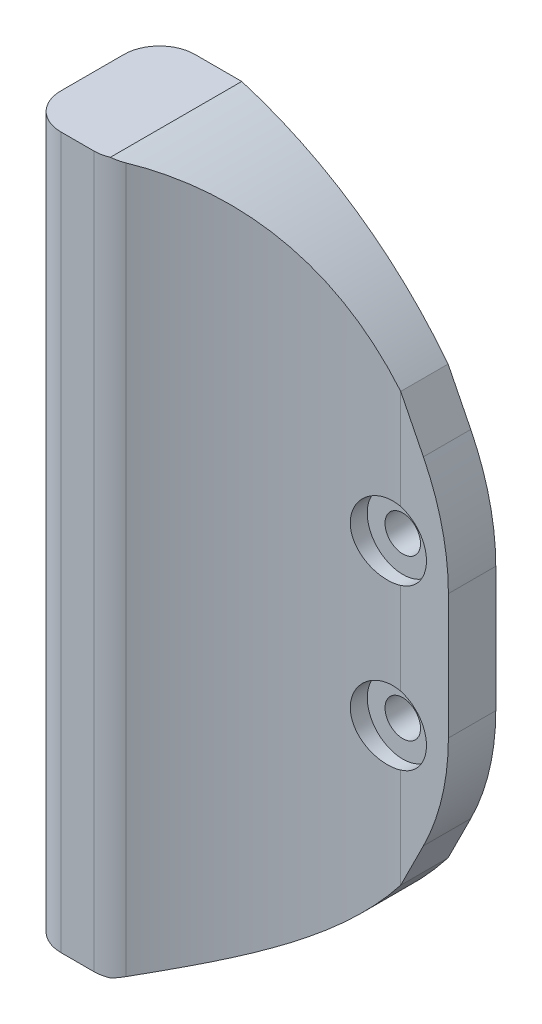
SolidWorks part; units mm, degrees
ref_plane "前视基准面" through (0, 0, 0) normal (0, 0, 1) x (1, 0, 0)
ref_plane "上视基准面" through (0, 0, 0) normal (0, 1, 0) x (1, 0, 0)
ref_plane "右视基准面" through (0, 0, 0) normal (1, 0, 0) x (0, 0, -1)
other "Configuration Table"
sketch "草图1" plane through (0, 0, 0) normal (0, 0, 1) x (1, 0, 0)
  line L1 (-17.6586, 30) -> (17.6586, 30)
  line L2 (-17.6586, 30) -> (-17.6586, -30)
  line L3 (-17.6586, -30) -> (17.6586, -30)
  line L4 (17.6586, 30) -> (17.6586, -30)
  line L5 (-17.6586, 30) -> (17.6586, -30) construction
  line L6 (-17.6586, -30) -> (17.6586, 30) construction
  circle A0 centre (0, 13.5) radius 1.5
  circle A1 centre (11.6913, 6.75) radius 1.5
  circle A2 centre (11.6913, -6.75) radius 1.5
  circle A3 centre (0, -13.5) radius 1.5
  circle A4 centre (-11.6913, -6.75) radius 1.5
  circle A5 centre (-11.6913, 6.75) radius 1.5
  point P14 (0, 0)
  point P18 (0, 0)
  dimension "D1" = 3
  dimension "D3" = 27
  dimension "D4" = 60
  dimension "D2" = 6
extrude "凸台-拉伸1" add sketch "草图1" along normal blind 8
sketch "草图2" plane through (0, 0, 8) normal (0, 0, 1) x (1, 0, 0)
  circle A0 centre (0, 13.5) radius 3
  circle A1 centre (11.6913, 6.75) radius 3
  circle A2 centre (11.6913, -6.75) radius 3
  circle A3 centre (0, -13.5) radius 3
  circle A4 centre (-11.6913, -6.75) radius 3
  circle A5 centre (-11.6913, 6.75) radius 3
  point P15 (0, 0)
  dimension "D1" = 6
  dimension "D2" = 6
extrude "切除-拉伸1" cut sketch "草图2" against normal blind 3
sketch "草图3" plane through (0, -30, 0) normal (0, -1, 0) x (1, 0, 0)
  line L0 (-17.6586, 0) -> (-35.2322, 0)
  line L1 (-35.2322, 0) -> (-35.2322, 11.3245)
  line L2 (-35.2322, 11.3245) -> (-23.3035, 11.3245)
  line L3 (-23.3035, 11.3245) -> (-17.6586, 8)
  line L4 (-17.6586, 0) -> (17.6586, 0)
  line L5 (17.6586, 0) -> (17.6586, 8)
  line L6 (17.6586, 8) -> (-17.6586, 8)
  line L7 (-17.6586, 8) -> (-17.6586, 0)
  line L8 (-17.6586, 0) -> (17.6586, 0)
  line L9 (17.6586, 0) -> (17.6586, 8)
  line L10 (17.6586, 8) -> (-17.6586, 8)
  line L11 (-17.6586, 8) -> (-17.6586, 0)
  line M9 (-17.6586, 8) -> (-17.6586, 0)
  dimension "D1" = 0
extrude "凸台-拉伸2" add sketch "草图3" against normal up to surface (60 mm away) contours L3 L2 L1 L0 M9 up to face at (0, 30, 4)
fillet "圆角1" radius 3 6 edges at (17.6586, 30, 4) (17.6586, -30, 4) (-17.6586, 0, 8) (-23.3035, 0, 11.3245) (-35.2322, 0, 0) (-35.2322, 0, 11.3245)
sketch "草图4" plane through (0, 0, 8) normal (0, 0, 1) x (1, 0, 0)
  circle A0 centre (0, 0) radius 5
  dimension "D1" = 10
extrude "切除-拉伸2" cut sketch "草图4" against normal through all
sketch "草图5" plane through (0, 0, 8) normal (0, 0, 1) x (1, 0, 0)
  line L0 (17.6586, -27) -> (17.6586, 27) construction
  line L1 (14.6586, 30) -> (-16.8409, 30) construction
  line L2 (-16.8409, -30) -> (14.6586, -30) construction
  line L3 (-16.8409, 30) -> (-18.3633, 30) construction
  line L4 (-18.3633, 30) -> (-18.3633, -30) construction
  line L5 (-18.3633, -30) -> (-16.8409, -30) construction
  line L6 (17.6586, -27) -> (17.6586, 27)
  line L7 (14.6586, 30) -> (-16.8409, 30)
  line L8 (-16.8409, -30) -> (14.6586, -30)
  line L9 (-16.8409, 30) -> (-18.3633, 30)
  line L10 (-18.3633, 30) -> (-18.3633, -30)
  line L11 (-18.3633, -30) -> (-16.8409, -30)
  line L12 (0, 0) -> (-13.5575, 0) construction
  line L13 (-16.8409, 30) -> (-6.8409, 10)
  line L14 (-6.8409, 10) -> (-6.8409, -10)
  line L15 (-16.8409, 30) -> (-16.8409, -30) construction
  line L16 (-16.8409, -30) -> (-6.8409, -10)
  arc A0 (17.6586, 27) -> (14.6586, 30) centre (14.6586, 27) ccw construction
  arc A1 (14.6586, -30) -> (17.6586, -27) centre (14.6586, -27) ccw construction
  arc A2 (17.6586, 27) -> (14.6586, 30) centre (14.6586, 27) ccw
  arc A3 (14.6586, -30) -> (17.6586, -27) centre (14.6586, -27) ccw
  point P11 (-7.5293, 11.3203)
  point P20 (-6.8409, 0)
  circle M4 centre (0, 0) radius 5
  circle M5 centre (0, 13.5) radius 3
  circle M8 centre (0, -13.5) radius 3
  circle M9 centre (11.6913, -6.75) radius 3
  circle M10 centre (11.6913, 6.75) radius 3
  line M11 (17.6586, -27) -> (17.6586, 27)
  arc M12 (17.6586, 27) -> (14.6586, 30) centre (14.6586, 27) ccw
  line M13 (14.6586, 30) -> (-16.8409, 30)
  line M15 (-16.8409, -30) -> (14.6586, -30)
  arc M16 (14.6586, -30) -> (17.6586, -27) centre (14.6586, -27) ccw
  dimension "D1" = 10
  dimension "D2" = 10
extrude "切除-拉伸3" cut sketch "草图5" against normal blind 10 contours L12 L14 L16 M11 M4 M15 M16 M8 M9 | L12 L6 L13 L14 M12 M13 M4 M5 M10 | M5 | M10 | M9 | M8
fillet "圆角2" radius 20 2 edges at (-6.8409, 10, 4) (-6.8409, -10, 4)
sketch "草图6" plane through (0, -30, 0) normal (0, -1, 0) x (1, 0, 0)
  line L0 (-8.9523, 0) -> (-6.8409, 0) construction
  line L1 (-6.8409, 0) -> (-6.8409, 8) construction
  line L2 (-6.8409, 8) -> (-8.9523, 8) construction
  line L3 (-16.8409, 0) -> (-8.9523, 0) construction
  line L4 (-8.9523, 8) -> (-16.8409, 8) construction
  line L5 (-16.8409, 0) -> (-16.8409, 8)
  line L6 (-18.3633, 8.415) -> (-22.5989, 10.9095)
  line L7 (-24.1213, 11.3245) -> (-32.2322, 11.3245)
  line L8 (-35.2322, 8.3245) -> (-35.2322, 3)
  line L9 (-32.2322, 0) -> (-16.8409, 0)
  line L10 (-16.8409, 0) -> (-16.8409, 8)
  line L11 (-18.3633, 8.415) -> (-22.5989, 10.9095)
  line L12 (-24.1213, 11.3245) -> (-32.2322, 11.3245)
  line L13 (-35.2322, 8.3245) -> (-35.2322, 3)
  line L14 (-32.2322, 0) -> (-16.8409, 0)
  line L15 (-16.8409, 8) -> (-16.8409, 0) construction
  line L16 (-8.9523, 0) -> (-6.8409, 0)
  line L17 (-6.8409, 0) -> (-6.8409, 8)
  line L18 (-6.8409, 8) -> (-8.9523, 8)
  line L19 (-16.8409, 0) -> (-8.9523, 0)
  line L20 (-8.9523, 8) -> (-16.8409, 8)
  line L21 (-16.8409, 8) -> (-16.8409, 0)
  line L22 (-18.3633, 8.415) -> (-10.8668, 4)
  line L23 (-10.8668, 4) -> (-6.8409, 4)
  line L24 (-28.2857, 11.3245) -> (-10.8668, 4)
  arc A4 (-18.3633, 8.415) -> (-16.8409, 8) centre (-16.8409, 11) ccw
  arc A5 (-22.5989, 10.9095) -> (-24.1213, 11.3245) centre (-24.1213, 8.3245) ccw
  arc A6 (-32.2322, 11.3245) -> (-35.2322, 8.3245) centre (-32.2322, 8.3245) ccw
  arc A7 (-35.2322, 3) -> (-32.2322, 0) centre (-32.2322, 3) ccw
  arc A8 (-18.3633, 8.415) -> (-16.8409, 8) centre (-16.8409, 11) ccw
  arc A9 (-22.5989, 10.9095) -> (-24.1213, 11.3245) centre (-24.1213, 8.3245) ccw
  arc A10 (-32.2322, 11.3245) -> (-35.2322, 8.3245) centre (-32.2322, 8.3245) ccw
  arc A11 (-35.2322, 3) -> (-32.2322, 0) centre (-32.2322, 3) ccw
  point P18 (-10.8668, 4)
  arc M13 (-16.8409, 8) -> (-18.3633, 8.415) centre (-16.8409, 11) cw
  line M14 (-18.3633, 8.415) -> (-22.5989, 10.9095)
  arc M15 (-22.5989, 10.9095) -> (-24.1213, 11.3245) centre (-24.1213, 8.3245) ccw
  line M16 (-24.1213, 11.3245) -> (-32.2322, 11.3245)
  dimension "D2" = 4
  dimension "D1" = 0
extrude "切除-拉伸4" cut sketch "草图6" against normal through all contours L22 L21 M13 | L22 L23 L17 L18 L20 L21 | L24 L21 L22 M16 M14 M15 | L21 L24 L22
sketch "草图7" plane through (0, 0, 5) normal (0, 0, 1) x (1, 0, 0)
  line L0 (-13.2449, -9.3164) -> (-13.2449, -4.1836) construction
  line L1 (-13.2449, 4.1836) -> (-13.2449, 9.3164) construction
  line L2 (-13.2449, -9.3164) -> (-13.2449, -4.1836)
  line L3 (-13.2449, 4.1836) -> (-13.2449, 9.3164)
  arc A0 (-13.2449, -4.1836) -> (-13.2449, -9.3164) centre (-11.6913, -6.75) ccw construction
  arc A1 (-13.2449, 9.3164) -> (-13.2449, 4.1836) centre (-11.6913, 6.75) ccw construction
  arc A2 (-13.2449, -4.1836) -> (-13.2449, -9.3164) centre (-11.6913, -6.75) ccw
  arc A3 (-13.2449, 9.3164) -> (-13.2449, 4.1836) centre (-11.6913, 6.75) ccw
  circle A4 centre (-11.6913, 6.75) radius 3
  circle A5 centre (-11.6913, -6.75) radius 3
  line M1 (-13.2449, 4.1836) -> (-13.2449, 9.3164)
  arc M2 (-13.2449, 9.3164) -> (-13.2449, 4.1836) centre (-11.6913, 6.75) ccw
extrude "切除-拉伸5" cut sketch "草图7" against normal blind 2 contours A4 M1 | M2 M1 | L2 A2 | L2 A5
sketch "草图8" plane through (0, 0, 11.3245) normal (0, 0, 1) x (1, 0, 0)
  line L0 (-10.8668, -18.0518) -> (-8.9523, -14.2229) construction
  line L1 (-6.8409, -5.2786) -> (-6.8409, 5.2786) construction
  line L2 (-8.9523, 14.2229) -> (-10.8668, 18.0518) construction
  line L3 (-10.8668, 18.0518) -> (-16.8409, 30) construction
  line L4 (-32.2322, -30) -> (-28.2857, -30)
  line L5 (-28.2857, -30) -> (-28.2857, 30)
  line L6 (-28.2857, 30) -> (-32.2322, 30)
  line L7 (-32.2322, 30) -> (-32.2322, -30)
  line L8 (-32.2322, -30) -> (-28.2857, -30)
  line L9 (-28.2857, -30) -> (-28.2857, 30)
  line L10 (-28.2857, 30) -> (-32.2322, 30)
  line L11 (-32.2322, 30) -> (-32.2322, -30)
  line L12 (-16.8409, 30) -> (-28.2857, 30) construction
  line L13 (-28.2857, 30) -> (-28.2857, -30) construction
  line L14 (-28.2857, -30) -> (-16.8409, -30) construction
  line L15 (-16.8409, -30) -> (-10.8668, -18.0518) construction
  line L16 (-10.8668, -18.0518) -> (-8.9523, -14.2229)
  line L17 (-6.8409, -5.2786) -> (-6.8409, 5.2786)
  line L18 (-8.9523, 14.2229) -> (-10.8668, 18.0518)
  line L19 (-10.8668, 18.0518) -> (-16.8409, 30)
  line L20 (-16.8409, 30) -> (-28.2857, 30)
  line L21 (-28.2857, 30) -> (-28.2857, -30)
  line L22 (-28.2857, -30) -> (-16.8409, -30)
  line L23 (-16.8409, -30) -> (-10.8668, -18.0518)
  line L24 (-6.8409, 0) -> (-28.2857, 0)
  arc A0 (-10.8668, 3.8655) -> (-10.8668, 9.6345) centre (-11.6913, 6.75) ccw construction
  arc A1 (-10.8668, -9.6345) -> (-10.8668, -3.8655) centre (-11.6913, -6.75) ccw construction
  arc A2 (-8.9523, -14.2229) -> (-6.8409, -5.2786) centre (-26.8409, -5.2786) ccw construction
  arc A3 (-6.8409, 5.2786) -> (-8.9523, 14.2229) centre (-26.8409, 5.2786) ccw construction
  arc A4 (-10.8668, 9.6345) -> (-10.8668, 3.8655) centre (-11.6913, 6.75) ccw construction
  arc A5 (-10.8668, -3.8655) -> (-10.8668, -9.6345) centre (-11.6913, -6.75) ccw construction
  circle A6 centre (-11.6913, -6.75) radius 3 construction
  arc A7 (-10.8668, 3.8655) -> (-10.8668, 9.6345) centre (-11.6913, 6.75) ccw
  arc A8 (-10.8668, -9.6345) -> (-10.8668, -3.8655) centre (-11.6913, -6.75) ccw
  arc A9 (-8.9523, -14.2229) -> (-6.8409, -5.2786) centre (-26.8409, -5.2786) ccw
  arc A10 (-6.8409, 5.2786) -> (-8.9523, 14.2229) centre (-26.8409, 5.2786) ccw
  arc A11 (-10.8668, 9.6345) -> (-10.8668, 3.8655) centre (-11.6913, 6.75) ccw
  arc A12 (-10.8668, -3.8655) -> (-10.8668, -9.6345) centre (-11.6913, -6.75) ccw
  circle A13 centre (-11.6913, -6.75) radius 3
  arc A14 (-10.8668, -18.0518) -> (-28.2857, -30) centre (-38.1835, 3.101) cw
  arc A15 (-10.8668, 18.0518) -> (-28.2857, 30) centre (-38.1835, -3.101) ccw
  dimension "D1" = 0
extrude "切除-拉伸6" cut sketch "草图8" against normal through all contours A15 L19 L20 | L23 A14 L22
sketch "草图10" plane through (0, -30, 0) normal (0, -1, 0) x (1, 0, 0)
  line L0 (-6.8409, 4) -> (-8.9523, 4) construction
  line L1 (-8.9523, 0) -> (-6.8409, 0) construction
  line L2 (-6.8409, 0) -> (-6.8409, 4) construction
  line L3 (-10.8668, 0) -> (-8.9523, 0) construction
  line L4 (-8.9523, 4) -> (-10.8668, 4) construction
  line L5 (-28.2857, 0) -> (-10.8668, 0) construction
  line L6 (-10.8668, 4) -> (-28.2857, 11.3245) construction
  line L7 (-32.2322, 0) -> (-28.2857, 0) construction
  line L8 (-28.2857, 11.3245) -> (-32.2322, 11.3245) construction
  line L9 (-35.2322, 8.3245) -> (-35.2322, 3) construction
  line L10 (-6.8409, 4) -> (-8.9523, 4)
  line L11 (-8.9523, 0) -> (-6.8409, 0)
  line L12 (-6.8409, 0) -> (-6.8409, 4)
  line L13 (-10.8668, 0) -> (-8.9523, 0)
  line L14 (-8.9523, 4) -> (-10.8668, 4)
  line L15 (-28.2857, 0) -> (-10.8668, 0)
  line L16 (-10.8668, 4) -> (-28.2857, 11.3245)
  line L17 (-32.2322, 0) -> (-28.2857, 0)
  line L18 (-28.2857, 11.3245) -> (-32.2322, 11.3245)
  line L19 (-35.2322, 8.3245) -> (-35.2322, 3)
  arc A0 (-32.2322, 11.3245) -> (-35.2322, 8.3245) centre (-32.2322, 8.3245) ccw construction
  arc A1 (-35.2322, 3) -> (-32.2322, 0) centre (-32.2322, 3) ccw construction
  arc A2 (-32.2322, 11.3245) -> (-35.2322, 8.3245) centre (-32.2322, 8.3245) ccw
  arc A3 (-35.2322, 3) -> (-32.2322, 0) centre (-32.2322, 3) ccw
  arc A4 (-28.2857, 11.3245) -> (-10.8668, 4) centre (-9.7579, 31.0119) ccw
extrude "切除-拉伸7" cut sketch "草图10" against normal through all contours L16 A4
fillet "圆角4" radius 3 1 edges at (-28.2857, 0, 11.3245)
